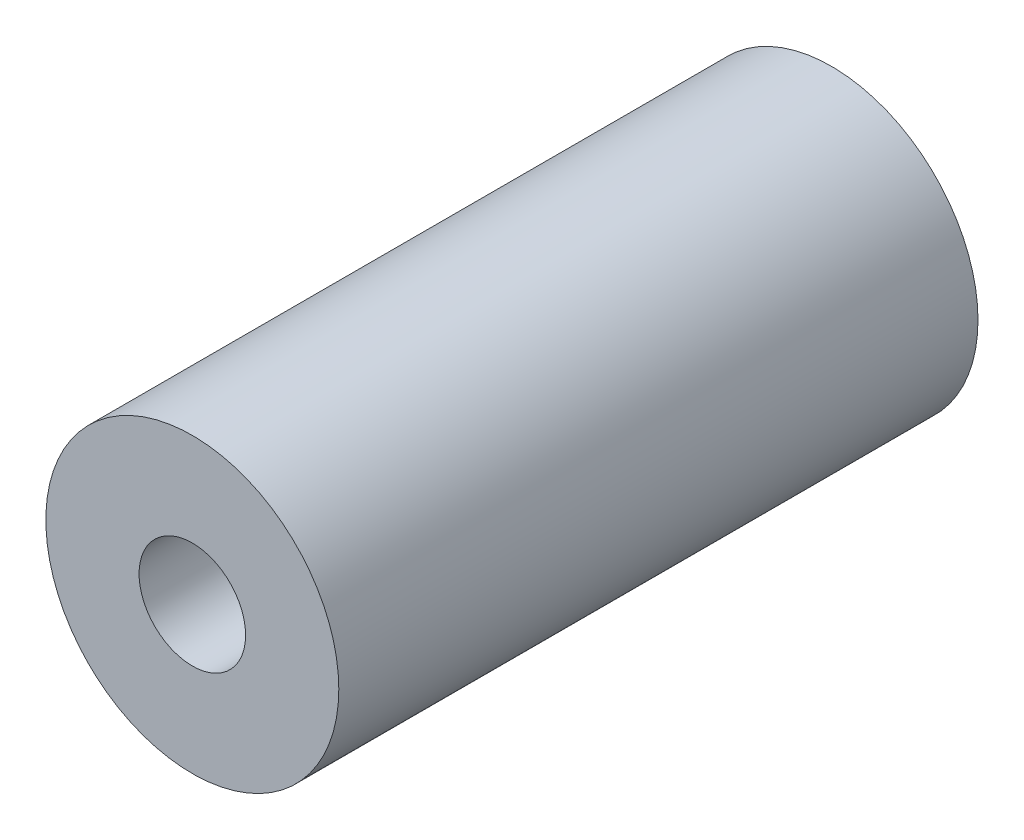
SolidWorks part; units mm, degrees
ref_plane "Płaszczyzna przednia" through (0, 0, 0) normal (0, 0, 1) x (1, 0, 0)
ref_plane "Płaszczyzna górna" through (0, 0, 0) normal (0, 1, 0) x (1, 0, 0)
ref_plane "Płaszczyzna prawa" through (0, 0, 0) normal (1, 0, 0) x (0, 0, -1)
sketch "Sketch1" plane through (0, 0, 0) normal (0, 0, 1) x (1, 0, 0)
  circle A0 centre (0, 0) radius 2.75
  circle A1 centre (0, 0) radius 1
  dimension "D1" = 5.5
  dimension "D2" = 2
extrude "Boss-Extrude1" add sketch "Sketch1" along normal blind 12
